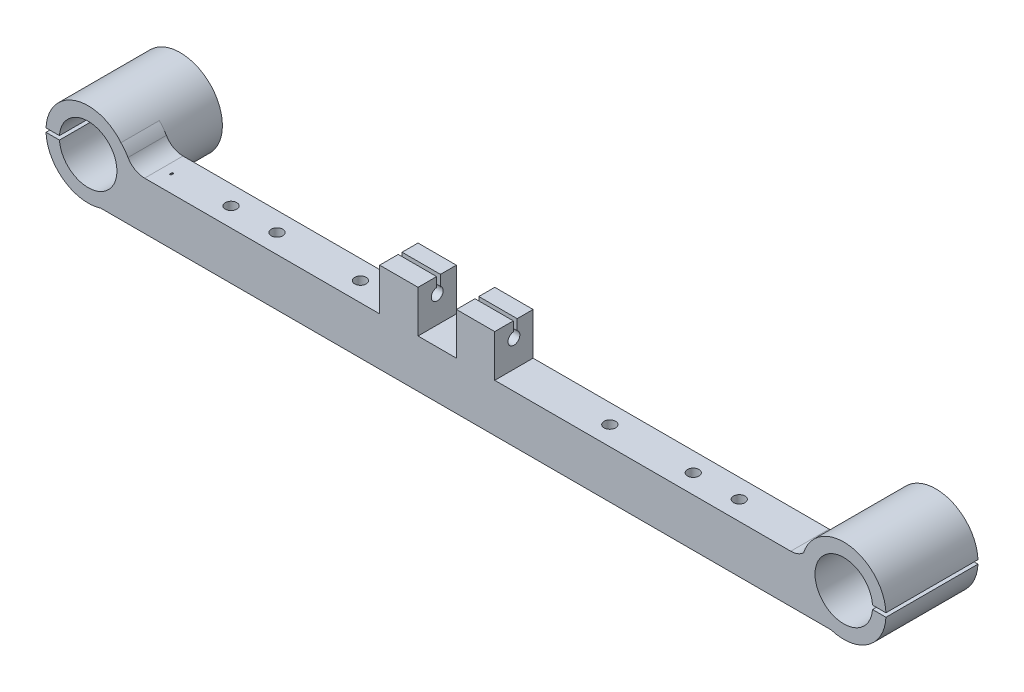
SolidWorks part; units mm, degrees
ref_plane "Front Plane" through (0, 0, 0) normal (0, 0, 1) x (1, 0, 0)
ref_plane "Top Plane" through (0, 0, 0) normal (0, 1, 0) x (1, 0, 0)
ref_plane "Right Plane" through (0, 0, 0) normal (1, 0, 0) x (0, 0, -1)
sketch "Sketch2" plane through (0, 0, 0) normal (0, 0, 1) x (1, 0, 0)
  line L0 (-98.5, 1.8316) -> (98.5, 1.8316) construction
  line L5 (-22.5, 3.8316) -> (-22.5, 14.8316)
  line L6 (-22.5, 14.8316) -> (-12.5, 14.8316)
  line L7 (-98.5, -8.6684) -> (98.5, -8.6684)
  line L10 (-87.0218, 3.8316) -> (-22.5, 3.8316)
  line L13 (7.5, 14.8316) -> (7.5, 3.8316)
  line L14 (7.5, 3.8316) -> (88.1922, 3.8316)
  line L15 (-12.5, 14.8316) -> (-12.5, 3.8316)
  line L16 (-12.5, 3.8316) -> (-2.5, 3.8316)
  line L17 (-2.5, 3.8316) -> (-2.5, 14.8316)
  line L18 (-2.5, 14.8316) -> (7.5, 14.8316)
  circle A0 centre (-98.5, 1.8316) radius 7.5
  circle A1 centre (98.5, 1.8316) radius 7.5
  arc A2 (-98.5, 12.3316) -> (-98.5, -8.6684) centre (-98.5, 1.8316) ccw
  arc A3 (98.5, -8.6684) -> (98.5, 12.3316) centre (98.5, 1.8316) ccw
  arc A4 (-98.5, 12.3316) -> (-87.0218, 3.8316) centre (-98.5, 0.3316) cw
  arc A5 (98.5, 12.3316) -> (88.1922, 3.8316) centre (98.5, 1.8316) ccw
  point P0 (0, 0)
  point P10 (0, 1.8316)
  dimension "D1" = 15
  dimension "D3" = 3
  dimension "D9" = 12
  dimension "D2" = 197
  dimension "D4" = 12.5
  dimension "D5" = 22.5
  dimension "D6" = 30
  dimension "D7" = 11
  dimension "D8" = 10
extrude "Boss-Extrude1" add sketch "Sketch2" along normal blind 10
sketch "Sketch8" plane through (0, 3.8316, 0) normal (0, 1, 0) x (1, 0, 0)
  line L0 (-87.0218, -10) -> (88.1922, -10) construction
  line L1 (-87.0218, -10) -> (-87.0218, 0) construction
  line L2 (-32.5028, -5) -> (32.4972, -5) construction
  line L3 (-54.2498, -5) -> (-66.2498, -5) construction
  line L4 (66.2502, -5) -> (54.2502, -5) construction
  line L5 (88.1922, -10) -> (88.1922, 0) construction
  circle A0 centre (-66.2498, -5) radius 1.5
  circle A1 centre (-54.2498, -5) radius 1.5
  circle A2 centre (-32.5028, -5) radius 1.5
  circle A3 centre (32.4972, -5) radius 1.5
  circle A4 centre (54.2502, -5) radius 1.5
  circle A5 centre (66.2502, -5) radius 1.5
  point P16 (0.5852, -10)
  point P19 (-87.0218, -5)
  point P21 (60.2502, -5)
  dimension "D6" = 3
  dimension "D1" = 12
  dimension "D2" = 12
  dimension "D3" = 59.665
  dimension "D4" = 54.835
  dimension "D5" = 65
  dimension "D7" = 55.695
fillet "Fillet1" radius 5 1 edges at (88.1922, 3.8316, 5)
sketch "Sketch3" plane through (0, 0, 10) normal (0, 0, 1) x (1, 0, 0)
  circle A0 centre (-98.5, 1.8316) radius 7.5
  circle A1 centre (-98.5, 1.8316) radius 11
  dimension "D1" = 15
  dimension "D2" = 22
extrude "Boss-Extrude2" add sketch "Sketch3" against normal blind 24
mirror "Mirror1" about plane through (0, 0, 0) normal (1, 0, 0) of "Boss-Extrude2"
sketch "Sketch4" plane through (-22.5, 0, 0) normal (-1, 0, 0) x (0, 0, 1)
  line L0 (10, 14.8316) -> (0, 14.8316) construction
  circle A0 centre (5, 10.8058) radius 1.55
  point P4 (5, 14.8316)
  dimension "D1" = 3.1
extrude "Cut-Extrude1" cut sketch "Sketch4" against normal up to surface (30 mm away) up to face at (7.5, 9.3316, 5)
ref_plane "Plane1" through (110, 0, 0) normal (1, 0, 0) x (0, 0, -1)
sketch "Sketch6" plane through (110, 0, 0) normal (1, 0, 0) x (0, 0, -1)
  line L0 (-10, 12.8316) -> (-10, -9.1684) construction
  line L1 (-17.1743, 1.3316) -> (19.9382, 1.3316)
  line L2 (-17.1743, 1.3316) -> (-17.1743, 2.3316)
  line L3 (-17.1743, 2.3316) -> (19.9382, 2.3316)
  line L4 (19.9382, 1.3316) -> (19.9382, 2.3316)
  line L5 (-17.1743, 1.3316) -> (19.9382, 2.3316) construction
  line L6 (-17.1743, 2.3316) -> (19.9382, 1.3316) construction
  point P0 (1.3819, 1.8316)
  point P7 (-10, 1.8316)
  point P8 (-17.1743, 1.8316)
  dimension "D1" = 1
extrude "Cut-Extrude3" cut sketch "Sketch6" against normal blind 10
mirror "Mirror2" about plane through (0, 0, 0) normal (1, 0, 0) of "Cut-Extrude3"
sketch "Sketch7" plane through (0, 14.8316, 0) normal (0, 1, 0) x (1, 0, 0)
  line L1 (-26.2478, -5.1544) -> (10.4895, -5.1544)
  line L2 (-26.2478, -5.1544) -> (-26.2478, -4.1544)
  line L3 (-26.2478, -4.1544) -> (10.4895, -4.1544)
  line L4 (10.4895, -5.1544) -> (10.4895, -4.1544)
  line L5 (-26.2478, -5.1544) -> (10.4895, -4.1544) construction
  line L6 (-26.2478, -4.1544) -> (10.4895, -5.1544) construction
  dimension "D1" = 1
extrude "Cut-Extrude4" cut sketch "Sketch7" against normal blind 3
fillet "Fillet2" radius 5 1 edges at (-87.0218, 3.8316, 5)
sketch "Sketch9" plane through (0, 3.8316, 0) normal (0, 1, 0) x (1, 0, 0)
  line L1 (-81.0358, -5.8547) -> (-81.4521, -5.8547)
  line L2 (-81.0358, -5.8547) -> (-81.0358, -5.14)
  line L3 (-81.0358, -5.14) -> (-81.4521, -5.14)
  line L4 (-81.4521, -5.8547) -> (-81.4521, -5.14)
extrude "Cut-Extrude6" cut sketch "Sketch9" against normal blind 1
extrude "Cut-Extrude5" cut sketch "Sketch8" against normal blind 7
